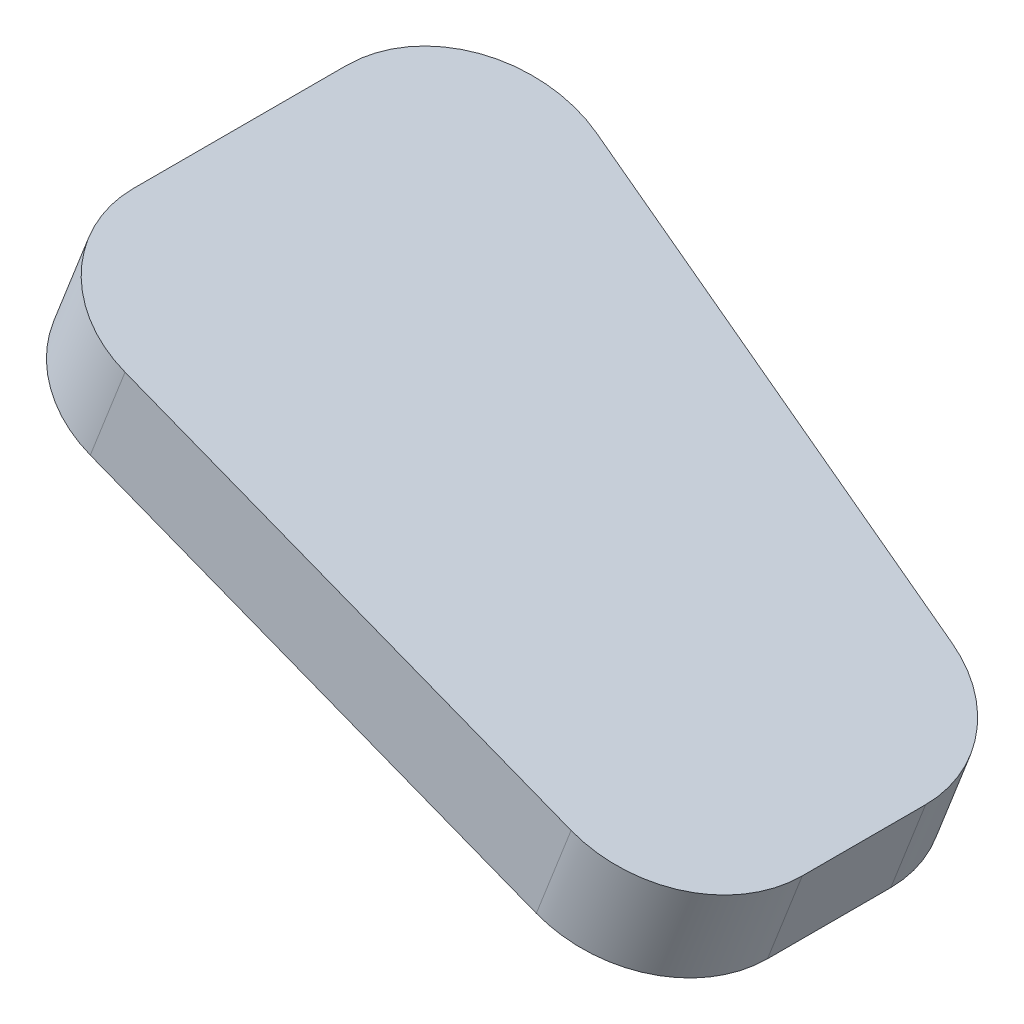
SolidWorks part; units mm, degrees
ref_plane "Front Plane" through (0, 0, 0) normal (0, 0, 1) x (1, 0, 0)
ref_plane "Top Plane" through (0, 0, 0) normal (0, 1, 0) x (1, 0, 0)
ref_plane "Right Plane" through (0, 0, 0) normal (1, 0, 0) x (0, 0, -1)
sketch "Sketch1" plane through (-4.899, -12.573, 0) normal (0.3631, 0.9318, 0) x (0.9318, -0.3631, 0)
  line L4 (-39.4733, -28.4158) -> (-26.7733, -28.4158)
  line L5 (-23.5983, -25.2408) -> (-23.5983, -21.9691)
  line L6 (-26.1849, -18.8491) -> (-38.8849, -16.4538)
  line L7 (-42.6483, -19.5738) -> (-42.6483, -25.2408)
  line L8 (-39.4733, -28.4158) -> (-26.7733, -28.4158)
  line L9 (-23.5983, -25.2408) -> (-23.5983, -21.9691)
  line L10 (-26.1849, -18.8491) -> (-38.8849, -16.4538)
  line L11 (-42.6483, -19.5738) -> (-42.6483, -25.2408)
  arc A4 (-42.6483, -25.2408) -> (-39.4733, -28.4158) centre (-39.4733, -25.2408) ccw
  arc A5 (-26.7733, -28.4158) -> (-23.5983, -25.2408) centre (-26.7733, -25.2408) ccw
  arc A6 (-23.5983, -21.9691) -> (-26.1849, -18.8491) centre (-26.7733, -21.9691) ccw
  arc A7 (-38.8849, -16.4538) -> (-42.6483, -19.5738) centre (-39.4733, -19.5738) ccw
  arc A8 (-42.6483, -25.2408) -> (-39.4733, -28.4158) centre (-39.4733, -25.2408) ccw
  arc A9 (-26.7733, -28.4158) -> (-23.5983, -25.2408) centre (-26.7733, -25.2408) ccw
  arc A10 (-23.5983, -21.9691) -> (-26.1849, -18.8491) centre (-26.7733, -21.9691) ccw
  arc A11 (-38.8849, -16.4538) -> (-42.6483, -19.5738) centre (-39.4733, -19.5738) ccw
  dimension "D1" = 0
extrude "Boss-Extrude1" add sketch "Sketch1" along normal blind 2.54
